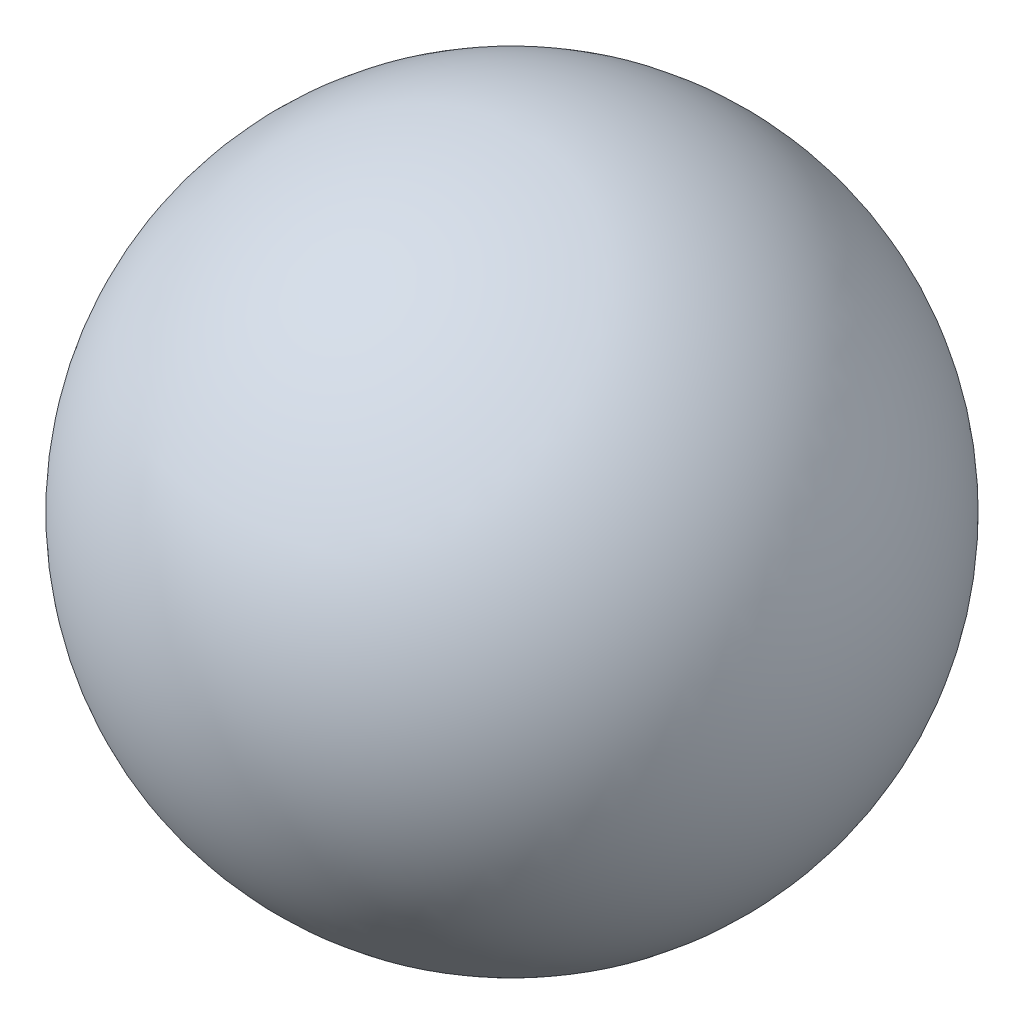
SolidWorks part; units mm, degrees
ref_plane "前视基准面" through (0, 0, 0) normal (0, 0, 1) x (1, 0, 0)
ref_plane "上视基准面" through (0, 0, 0) normal (0, 1, 0) x (1, 0, 0)
ref_plane "右视基准面" through (0, 0, 0) normal (1, 0, 0) x (0, 0, -1)
other "Configuration Table"
sketch "草图1" plane through (0, 0, 0) normal (0, 0, 1) x (1, 0, 0)
  line L0 (0, 0) -> (0, 240)
  arc A0 (0, 240) -> (0, 0) centre (0, 120) ccw
  dimension "D1" = 240
revolve "旋转1" add sketch "草图1" angle 360 about L0
